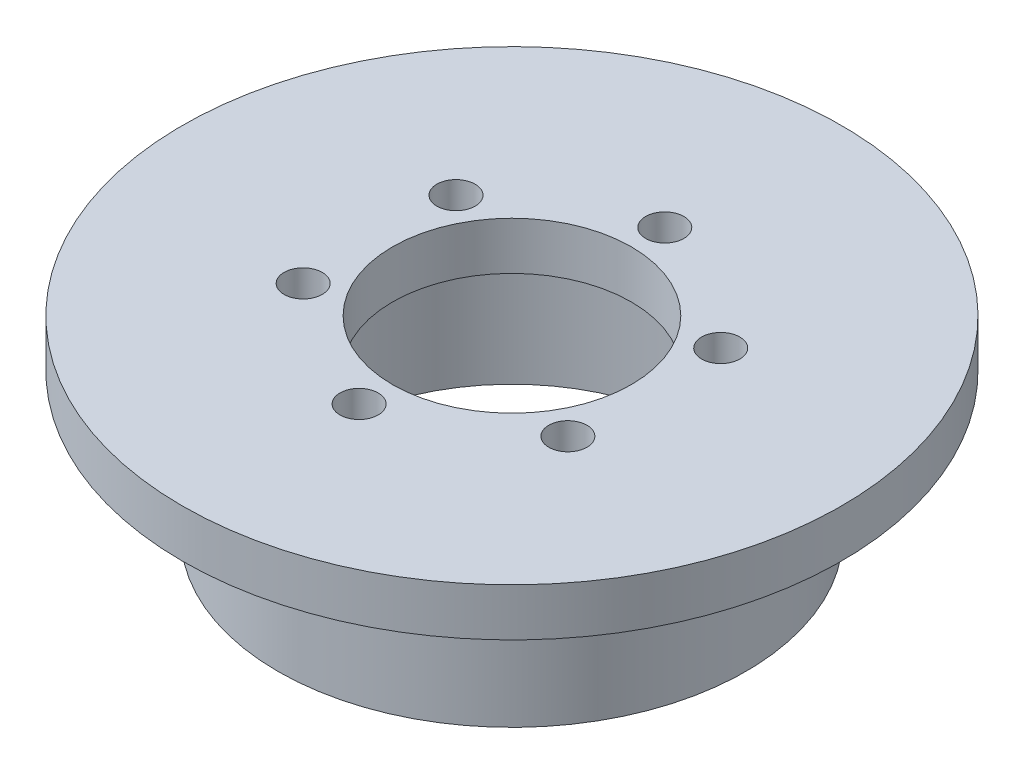
SolidWorks part; units mm, degrees
ref_plane "Alzado" through (0, 0, 0) normal (0, 0, 1) x (1, 0, 0)
ref_plane "Planta" through (0, 0, 0) normal (0, 1, 0) x (1, 0, 0)
ref_plane "Vista lateral" through (0, 0, 0) normal (1, 0, 0) x (0, 0, -1)
sketch "Croquis1" plane through (0, 0, 0) normal (0, 1, 0) x (1, 0, 0)
  circle A0 centre (0, 0) radius 34.5
  dimension "D1" = 69
extrude "Saliente-Extruir1" add sketch "Croquis1" along normal blind 5
sketch "Croquis2" plane through (0, 0, 0) normal (0, -1, 0) x (1, 0, 0)
  circle A0 centre (0, 0) radius 24.5
  circle A3 centre (0, 0) radius 19.5
  dimension "D1" = 49
  dimension "D2" = 5
extrude "Saliente-Extruir2" add sketch "Croquis2" along normal blind 15
sketch "Croquis4" plane through (0, 5, 0) normal (0, 1, 0) x (1, 0, 0)
  line L0 (0, 0) -> (0, 24.6395)
sketch "Croquis5" plane through (0, 0, 0) normal (0, -1, 0) x (1, 0, 0)
  circle A3 centre (0, 0) radius 12.5
  circle A4 centre (0, 0) radius 12.5
  dimension "D1" = 7
extrude "Cortar-Extruir2" cut sketch "Croquis5" against normal through all
sketch "Croquis7" plane through (0, 0, 0) normal (0, -1, 0) x (1, 0, 0)
  circle A0 centre (0, 0) radius 16 construction
  circle A2 centre (0, 0) radius 12.5 construction
  circle A3 centre (0, -16) radius 2
  dimension "D1" = 3.5
  dimension "D2" = 4
  dimension "D3" = 32
extrude "Cortar-Extruir3" cut sketch "Croquis7" against normal through all
pattern_circular "MatrizC1" count 6 over 360 about axis through (0, 0, 0) along (0, 1, 0) of "Cortar-Extruir3"
